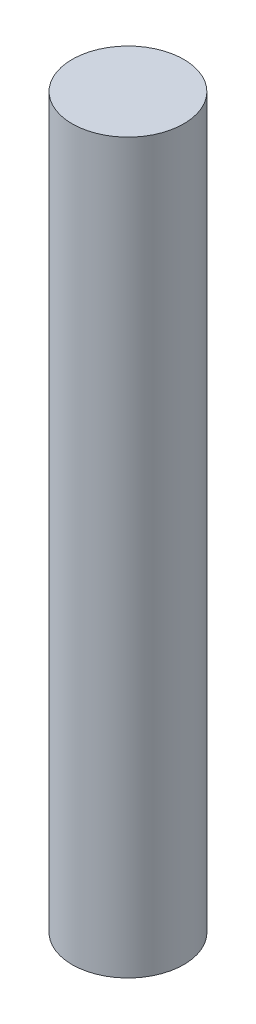
SolidWorks part; units mm, degrees
ref_plane "Front Plane" through (0, 0, 0) normal (0, 0, 1) x (1, 0, 0)
ref_plane "Top Plane" through (0, 0, 0) normal (0, 1, 0) x (1, 0, 0)
ref_plane "Right Plane" through (0, 0, 0) normal (1, 0, 0) x (0, 0, -1)
sketch "Sketch1" plane through (0, 0, 0) normal (0, 1, 0) x (1, 0, 0)
  circle A0 centre (0, 0) radius 1.15
  dimension "D1" = 2.3
extrude "Boss-Extrude1" add sketch "Sketch1" along normal blind 15
